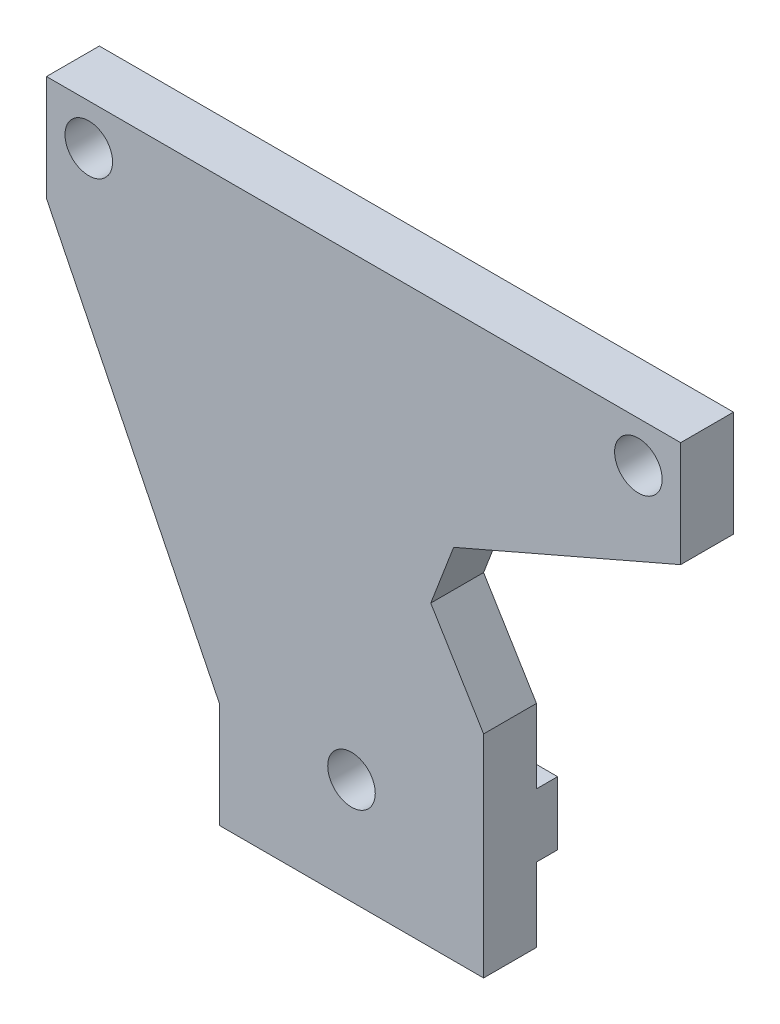
SolidWorks part; units mm, degrees
ref_plane "Plan de face" through (0, 0, 0) normal (0, 0, 1) x (1, 0, 0)
ref_plane "Plan de dessus" through (0, 0, 0) normal (0, 1, 0) x (1, 0, 0)
ref_plane "Plan de droite" through (0, 0, 0) normal (1, 0, 0) x (0, 0, -1)
sketch "Esquisse1" plane through (0, 0, 0) normal (0, 0, 1) x (1, 0, 0)
  line L0 (0, 0) -> (60, 0)
  line L1 (60, 0) -> (60, -10)
  line L2 (0, 0) -> (0, -10)
  line L3 (0, -10) -> (16.3569, -43.1881)
  line L4 (16.3569, -43.1881) -> (16.3569, -53.1881)
  line L5 (16.3569, -53.1881) -> (41.3569, -53.1881)
  line L6 (41.3569, -53.1881) -> (41.3569, -33.1881)
  line L8 (41.3569, -33.1881) -> (36.3557, -24.9678)
  line L9 (36.3557, -24.9678) -> (38.5227, -19.3147)
  line L10 (38.5227, -19.3147) -> (60, -10)
  dimension "D1" = 60
  dimension "D2" = 10
  dimension "D3" = 37
  dimension "D4" = 10
  dimension "D5" = 25
  dimension "D6" = 20
  dimension "D7" = 116.237
  dimension "D8" = 82.13
  dimension "D9" = 156.554
extrude "Boss.-Extru.1" add sketch "Esquisse1" along normal blind 5
sketch "Esquisse2" plane through (0, 0, 0) normal (0, 0, -1) x (-1, 0, 0)
  line L21 (-41.3569, -53.1881) -> (-41.3569, -33.1881) construction
  line L22 (-41.3569, -40.1881) -> (-16.3569, -40.1881)
  line L23 (-41.3569, -40.1881) -> (-41.3569, -46.1881)
  line L24 (-41.3569, -46.1881) -> (-16.3569, -46.1881)
  line L25 (-16.3569, -40.1881) -> (-16.3569, -46.1881)
  line L26 (-16.3569, -43.1881) -> (-16.3569, -53.1881) construction
  line L27 (-16.3569, -53.1881) -> (-41.3569, -53.1881) construction
  dimension "D4" = 6
  dimension "D5" = 7
extrude "Boss.-Extru.2" add sketch "Esquisse2" along normal blind 2
sketch "Esquisse3" plane through (0, 0, -2) normal (0, 0, -1) x (-1, 0, 0)
  line L0 (-56, -3.88) -> (-4, -3.88) construction
  line L2 (-60, -10) -> (-60, 0) construction
  line L4 (-60, 0) -> (0, 0) construction
  line L6 (-41.3569, -40.1881) -> (-41.3569, -46.1881) construction
  line L9 (-16.3569, -53.1881) -> (-41.3569, -53.1881) construction
  circle A3 centre (-28.8569, -43.1881) radius 2.25
  circle A4 centre (-56, -3.88) radius 2.25
  circle A5 centre (-4, -3.88) radius 2.25
  dimension "D3" = 4
  dimension "D6" = 4.5
  dimension "D1" = 4.5
  dimension "D2" = 52
  dimension "D4" = 3.88
  dimension "D5" = 12.5
  dimension "D7" = 10
extrude "Enlèv. mat.-Extru.3" cut sketch "Esquisse3" against normal blind 8.1
